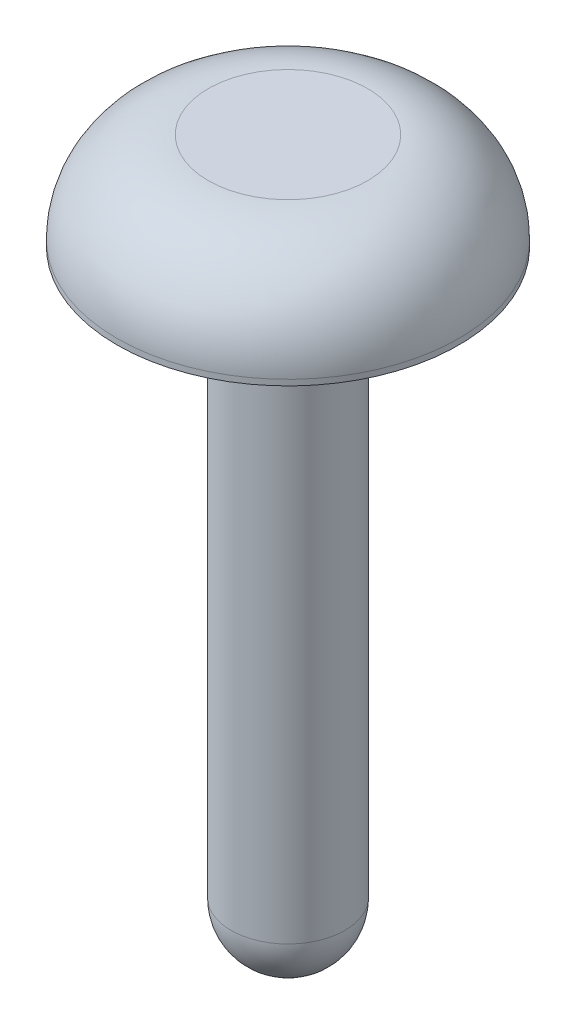
SolidWorks part; units mm, degrees
ref_plane "Alzado" through (0, 0, 0) normal (0, 0, 1) x (1, 0, 0)
ref_plane "Planta" through (0, 0, 0) normal (0, 1, 0) x (1, 0, 0)
ref_plane "Vista lateral" through (0, 0, 0) normal (1, 0, 0) x (0, 0, -1)
sketch "Croquis2" plane through (0, 0, 0) normal (0, 1, 0) x (1, 0, 0)
  circle A0 centre (0, 0) radius 1
extrude "Saliente-Extruir1" add sketch "Croquis2" along normal blind 12.6
fillet "Redondeo5" radius 1 1 edges at (0, 0, 1)
sketch "Croquis3" plane through (0, 12.6, 0) normal (0, 1, 0) x (1, 0, 0)
  circle A0 centre (0, 0) radius 3
  dimension "D1" = 6
extrude "Saliente-Extruir2" add sketch "Croquis3" along normal blind 0.0001 and the other way blind 1.7
fillet "Redondeo6" radius 1.6 1 edges at (0, 12.6001, 3)
sketch "Croquis4" plane through (0, 10.9, 0) normal (0, -1, 0) x (-1, 0, 0)
  circle A0 centre (0, 0) radius 2.5
  circle A4 centre (0, 0) radius 1
extrude "Cortar-Extruir6" cut sketch "Croquis4" against normal blind 1
